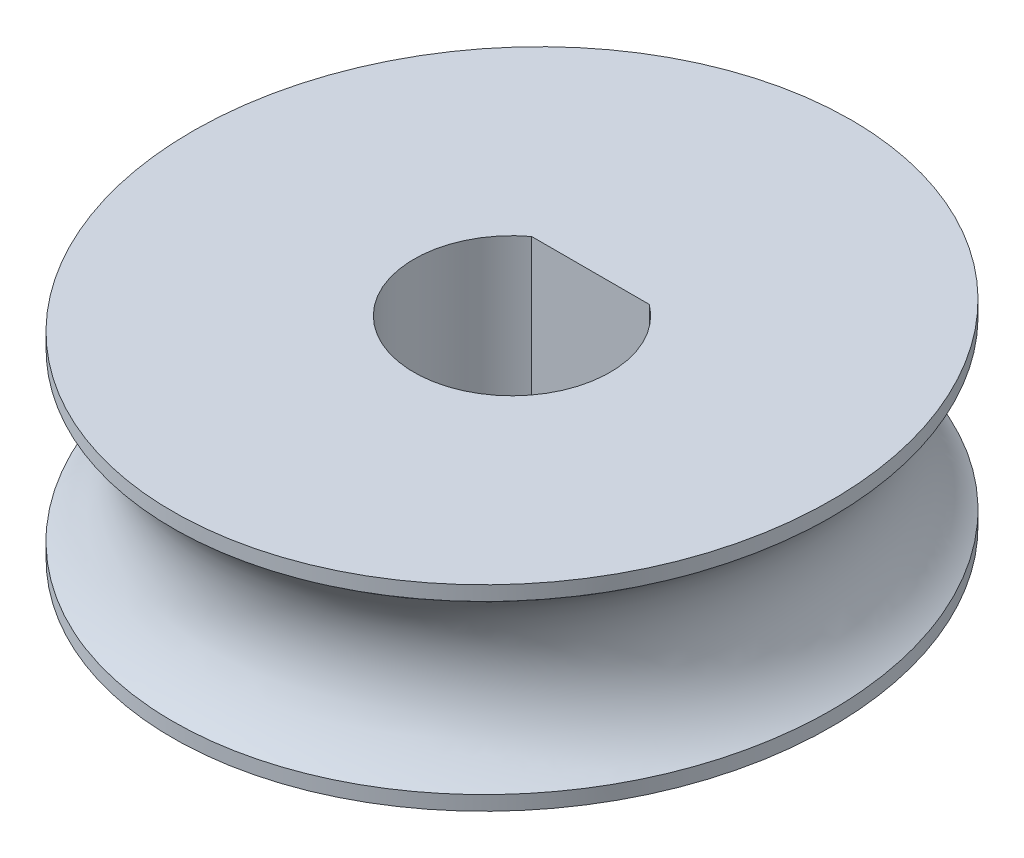
SolidWorks part; units mm, degrees
ref_plane "Front Plane" through (0, 0, 0) normal (0, 0, 1) x (1, 0, 0)
ref_plane "Top Plane" through (0, 0, 0) normal (0, 1, 0) x (1, 0, 0)
ref_plane "Right Plane" through (0, 0, 0) normal (1, 0, 0) x (0, 0, -1)
sketch "Sketch1" plane through (0, 0, 0) normal (0, 1, 0) x (1, 0, 0)
  line L0 (1.5, 2) -> (-1.5, 2)
  line L1 (0, 0) -> (0, -10) construction
  arc A0 (-1.5, 2) -> (1.5, 2) centre (0, 0) ccw
  ellipse E0 centre (0, 0) end of major axis (0, -10) minor radius 9.5
  dimension "D2" = 5
  dimension "D1" = 10
  dimension "D3" = 9.5
  dimension "D4" = 3
extrude "Boss-Extrude1" add sketch "Sketch1" along normal blind 5
ref_plane "Plane1" through (0, 2.5, 0) normal (0, 1, 0) x (1, 0, 0)
sketch "Sketch2" plane through (0, 2.5, 0) normal (0, 1, 0) x (1, 0, 0)
  ellipse E0 centre (0, 0) end of major axis (0, 10) minor radius 9.5
  ellipse E1 centre (0, 0) end of major axis (0, -10) minor radius 9.5 construction
  point P1 (0, 0)
  point P7 (-4.9902, -0.2473)
  point P15 (0, 0)
  point P16 (0, 0)
sweep "Cut-Sweep3" cut path "Sketch2" circular profile diameter 5.05 parameters "D3"=5.05
sketch "Sketch27" plane through (0, 5, 0) normal (0, 1, 0) x (1, 0, 0)
  line L0 (0, 8.6456) -> (0, 9.6456)
  line L1 (8.1456, 0) -> (9.1456, 0) construction
  ellipse E0 centre (0, 0) end of major axis (0, 8.6456) minor radius 8.1456
  spline S0 degree 3 poles (0, 9.6456) (-1.1947, 9.6456) (-2.3884, 9.3959) (-4.5999, 8.4316) (-5.6131, 7.719) (-7.308, 5.9349) (-7.9874, 4.8653) (-8.907, 2.5281) (-9.1456, 1.2649) (-9.1456, -1.2649) (-8.907, -2.5281) (-7.9874, -4.8653) (-7.308, -5.9349) (-5.6131, -7.719) (-4.5999, -8.4316) (-2.3884, -9.3959) (-1.1947, -9.6456) (1.1947, -9.6456) (2.3884, -9.3959) (4.5999, -8.4316) (5.6131, -7.719) (7.308, -5.9349) (7.9874, -4.8653) (8.907, -2.5281) (9.1456, -1.2649) (9.1456, 1.2649) (8.907, 2.5281) (7.9874, 4.8653) (7.308, 5.9349) (5.6131, 7.719) (4.5999, 8.4316) (2.3884, 9.3959) (1.1947, 9.6456) (0, 9.6456) (-1.1947, 9.6456) (-2.3884, 9.3959) knots -0.0625 0 0 0 0.0625 0.0625 0.125 0.125 0.1875 0.1875 0.25 0.25 0.3125 0.3125 0.375 0.375 0.4375 0.4375 0.5 0.5 0.5625 0.5625 0.625 0.625 0.6875 0.6875 0.75 0.75 0.8125 0.8125 0.875 0.875 0.9375 0.9375 1 1 1 1.0625 1.0625 1.125 weights 0.502488 0.502488 0.502488 0.502488 0.502488 0.502488 0.502488 0.502488 0.502488 0.502488 0.502488 0.502488 0.502488 0.502488 0.502488 0.502488 0.502488 0.502488 0.502488 0.502488 0.502488 0.502488 0.502488 0.502488 0.502488 0.502488 0.502488 0.502488 0.502488 0.502488 0.502488 0.502488 0.502488 0.502488 0.502488 0.502488 only from (0, 9.6456) to (0, 9.6456) construction
  point P9 (0, 0)
  point P10 (8.6456, 0)
  point P17 (0, 0)
  point P18 (0, 9.6456)
  point P21 (0, 0)
  dimension "D1" = 1
  dimension "D2" = 1
extrude "Cut-Extrude1" cut sketch "Sketch27" against normal blind 10
